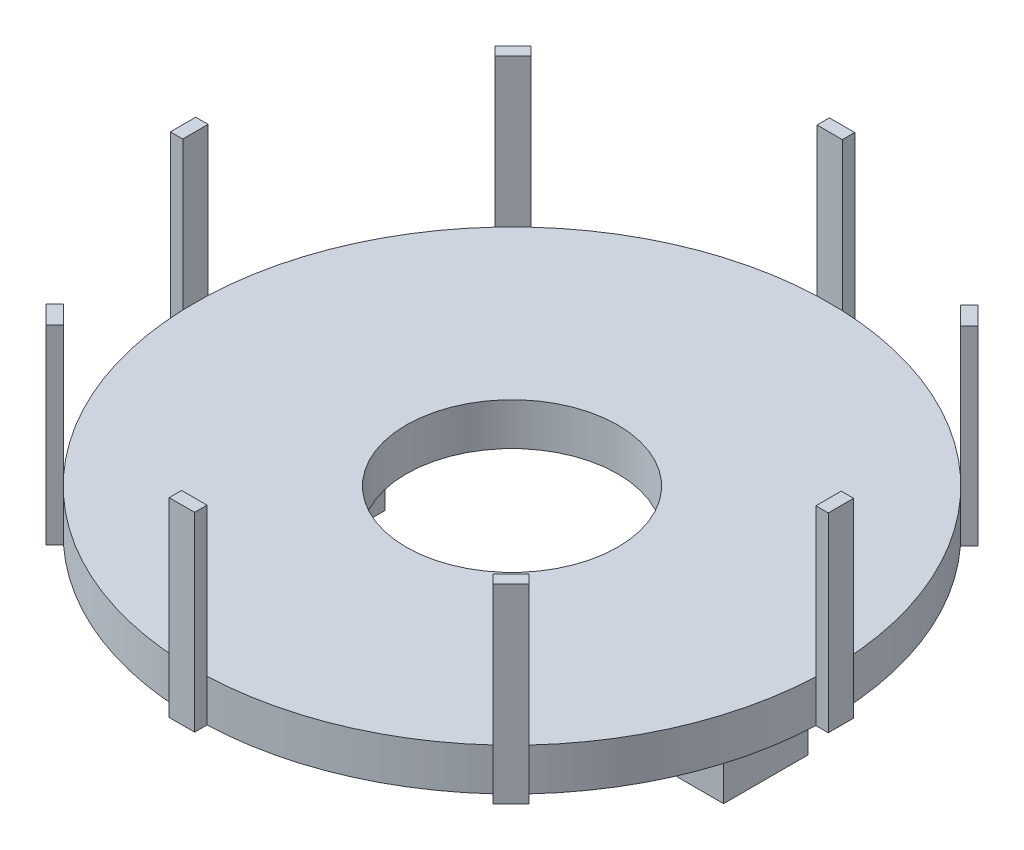
SolidWorks part; units mm, degrees
ref_plane "Front Plane" through (0, 0, 0) normal (0, 0, 1) x (1, 0, 0)
ref_plane "Top Plane" through (0, 0, 0) normal (0, 1, 0) x (1, 0, 0)
ref_plane "Right Plane" through (0, 0, 0) normal (1, 0, 0) x (0, 0, -1)
sketch "Sketch1" plane through (0, 0, 0) normal (0, 1, 0) x (1, 0, 0)
  circle A0 centre (0, 0) radius 75
extrude "Boss-Extrude1" add sketch "Sketch1" along normal blind 10 contours A0
sketch "Sketch2" plane through (0, 10, 0) normal (0, 1, 0) x (1, 0, 0)
  circle A0 centre (0, 0) radius 25
extrude "Cut-Extrude1" cut sketch "Sketch2" against normal blind 10
sketch "Sketch3" plane through (0, 0, 0) normal (0, -1, 0) x (1, 0, 0)
  line L1 (0, 0) -> (0, -75)
  line L2 (-40, -10) -> (-60, 10) construction
  line L3 (40, 10) -> (60, 10)
  line L4 (40, 10) -> (40, -10)
  line L5 (40, -10) -> (60, -10)
  line L6 (60, 10) -> (60, -10)
  line L7 (40, 10) -> (60, -10) construction
  line L8 (40, -10) -> (60, 10) construction
  line L9 (-40, 10) -> (-60, -10) construction
  line L10 (-60, 10) -> (-60, -10)
  line L11 (-40, -10) -> (-60, -10)
  line L12 (-40, 10) -> (-40, -10)
  line L13 (-40, 10) -> (-60, 10)
  circle A0 centre (0, 0) radius 75 construction
  point P7 (50, 0)
  point P16 (-50, 0)
  dimension "D1" = 20
  dimension "D2" = 20
  dimension "D3" = 50
extrude "Boss-Extrude2" add sketch "Sketch3" along normal blind 20 contours L6 L3 L4 L5 | L12 L13 L10 L11
sketch "Sketch4" plane through (0, -20, 0) normal (0, -1, 0) x (1, 0, 0)
  line L0 (0, 0) -> (0, 42.7777)
  circle A0 centre (-50, 0) radius 5.1
  circle A1 centre (50, 0) radius 5.1
extrude "Cut-Extrude2" cut sketch "Sketch4" against normal blind 20 contours A0 | A1
sketch "Sketch5" plane through (0, 10, 0) normal (0, 1, 0) x (1, 0, 0)
  line L0 (53.0339, 57.0879) -> (50.6819, 54.736)
  line L1 (53.0339, 57.0879) -> (57.2765, 52.8453)
  line L2 (57.2765, 52.8453) -> (54.9246, 50.4933)
  line L3 (-2.8667, 77.8679) -> (3.1333, 77.8679)
  line L4 (-2.8667, 77.8679) -> (-2.8667, 74.5417)
  line L5 (-2.8667, 74.5417) -> (3.1333, 74.5417)
  line L6 (3.1333, 77.8679) -> (3.1333, 74.5417)
  line L7 (-2.8667, 77.8679) -> (3.1333, 74.5417) construction
  line L8 (-2.8667, 74.5417) -> (3.1333, 77.8679) construction
  line L9 (50.6819, 54.736) -> (54.9246, 50.4933)
  line L10 (77.8679, 2.8667) -> (74.5417, 2.8667)
  line L11 (77.8679, 2.8667) -> (77.8679, -3.1333)
  line L12 (77.8679, -3.1333) -> (74.5417, -3.1333)
  line L13 (74.5417, 2.8667) -> (74.5417, -3.1333)
  line L14 (57.0879, -53.0339) -> (54.736, -50.6819)
  line L15 (57.0879, -53.0339) -> (52.8453, -57.2765)
  line L16 (52.8453, -57.2765) -> (50.4933, -54.9246)
  line L17 (54.736, -50.6819) -> (50.4933, -54.9246)
  line L18 (2.8667, -77.8679) -> (2.8667, -74.5417)
  line L19 (2.8667, -77.8679) -> (-3.1333, -77.8679)
  line L20 (-3.1333, -77.8679) -> (-3.1333, -74.5417)
  line L21 (2.8667, -74.5417) -> (-3.1333, -74.5417)
  line L22 (-53.0339, -57.0879) -> (-50.6819, -54.736)
  line L23 (-53.0339, -57.0879) -> (-57.2765, -52.8453)
  line L24 (-57.2765, -52.8453) -> (-54.9246, -50.4933)
  line L25 (-50.6819, -54.736) -> (-54.9246, -50.4933)
  line L26 (-77.8679, -2.8667) -> (-74.5417, -2.8667)
  line L27 (-77.8679, -2.8667) -> (-77.8679, 3.1333)
  line L28 (-77.8679, 3.1333) -> (-74.5417, 3.1333)
  line L29 (-74.5417, -2.8667) -> (-74.5417, 3.1333)
  line L30 (-57.0879, 53.0339) -> (-54.736, 50.6819)
  line L31 (-57.0879, 53.0339) -> (-52.8453, 57.2765)
  line L32 (-52.8453, 57.2765) -> (-50.4933, 54.9246)
  line L33 (-54.736, 50.6819) -> (-50.4933, 54.9246)
  point P6 (0.1333, 76.2048)
  point P38 (0, 0)
  dimension "D1" = 6
  dimension "D2" = 8
extrude "Boss-Extrude3" add sketch "Sketch5" against normal blind 10
sketch "Sketch6" plane through (0, 10, 0) normal (0, 1, 0) x (1, 0, 0)
  line L0 (0, 0) -> (0.1333, 77.8679)
  line L1 (3.1333, 77.8679) -> (-2.8667, 77.8679) construction
  line L2 (53.0339, 57.0879) -> (50.9597, 55.0137)
  line L3 (-2.8667, 77.8679) -> (3.1333, 77.8679)
  line L4 (-2.8667, 77.8679) -> (-2.8667, 74.9345)
  line L5 (-2.8667, 74.9345) -> (3.1333, 74.9345)
  line L6 (3.1333, 77.8679) -> (3.1333, 74.9345)
  line L7 (53.0339, 57.0879) -> (57.2765, 52.8453)
  line L8 (57.2765, 52.8453) -> (55.2023, 50.7711)
  line L9 (50.9597, 55.0137) -> (55.2023, 50.7711)
  line L10 (77.8679, 2.8667) -> (74.9345, 2.8667)
  line L11 (77.8679, 2.8667) -> (77.8679, -3.1333)
  line L12 (77.8679, -3.1333) -> (74.9345, -3.1333)
  line L13 (74.9345, 2.8667) -> (74.9345, -3.1333)
  line L14 (57.0879, -53.0339) -> (55.0137, -50.9597)
  line L15 (57.0879, -53.0339) -> (52.8453, -57.2765)
  line L16 (52.8453, -57.2765) -> (50.7711, -55.2023)
  line L17 (55.0137, -50.9597) -> (50.7711, -55.2023)
  line L18 (2.8667, -77.8679) -> (2.8667, -74.9345)
  line L19 (2.8667, -77.8679) -> (-3.1333, -77.8679)
  line L20 (-3.1333, -77.8679) -> (-3.1333, -74.9345)
  line L21 (2.8667, -74.9345) -> (-3.1333, -74.9345)
  line L22 (-53.0339, -57.0879) -> (-50.9597, -55.0137)
  line L23 (-53.0339, -57.0879) -> (-57.2765, -52.8453)
  line L24 (-57.2765, -52.8453) -> (-55.2023, -50.7711)
  line L25 (-50.9597, -55.0137) -> (-55.2023, -50.7711)
  line L26 (-77.8679, -2.8667) -> (-74.9345, -2.8667)
  line L27 (-77.8679, -2.8667) -> (-77.8679, 3.1333)
  line L28 (-77.8679, 3.1333) -> (-74.9345, 3.1333)
  line L29 (-74.9345, -2.8667) -> (-74.9345, 3.1333)
  line L30 (-57.0879, 53.0339) -> (-55.0137, 50.9597)
  line L31 (-57.0879, 53.0339) -> (-52.8453, 57.2765)
  line L32 (-52.8453, 57.2765) -> (-50.7711, 55.2023)
  line L33 (-55.0137, 50.9597) -> (-50.7711, 55.2023)
  point P41 (0, 0)
  line M6 (-50.7711, 55.2023) -> (-52.8453, 57.2765)
  line M7 (-52.8453, 57.2765) -> (-57.0879, 53.0339)
  line M8 (-57.0879, 53.0339) -> (-55.0213, 50.9672)
  line M14 (-55.2023, -50.7711) -> (-57.2765, -52.8453)
  line M15 (-57.2765, -52.8453) -> (-53.0339, -57.0879)
  line M16 (-53.0339, -57.0879) -> (-50.9672, -55.0213)
  line M18 (-3.1333, -74.9345) -> (-3.1333, -77.8679)
  line M19 (-3.1333, -77.8679) -> (2.8667, -77.8679)
  line M20 (2.8667, -77.8679) -> (2.8667, -74.9452)
  line M22 (50.7711, -55.2023) -> (52.8453, -57.2765)
  line M23 (52.8453, -57.2765) -> (57.0879, -53.0339)
  line M24 (57.0879, -53.0339) -> (55.0213, -50.9672)
  line M26 (74.9345, -3.1333) -> (77.8679, -3.1333)
  line M27 (77.8679, -3.1333) -> (77.8679, 2.8667)
  line M28 (77.8679, 2.8667) -> (74.9452, 2.8667)
  line M30 (55.2023, 50.7711) -> (57.2765, 52.8453)
  line M31 (57.2765, 52.8453) -> (53.0339, 57.0879)
  line M32 (53.0339, 57.0879) -> (50.9672, 55.0213)
  line M34 (3.1333, 74.9345) -> (3.1333, 77.8679)
  line M35 (3.1333, 77.8679) -> (-2.8667, 77.8679)
  line M36 (-2.8667, 77.8679) -> (-2.8667, 74.9452)
  dimension "D1" = 8
extrude "Boss-Extrude4" add sketch "Sketch6" along normal blind 35 contours L4 L5 L0 M35 M36 | L0 L5 M34 M35 | L30 L33 M6 M7 M8 | L22 L25 M14 M15 M16 | L18 L21 M18 M19 M20 | L14 L17 M22 M23 M24 | L10 L13 M26 M27 M28 | L2 L9 M30 M31 M32 | L27 L28 L29 L26
